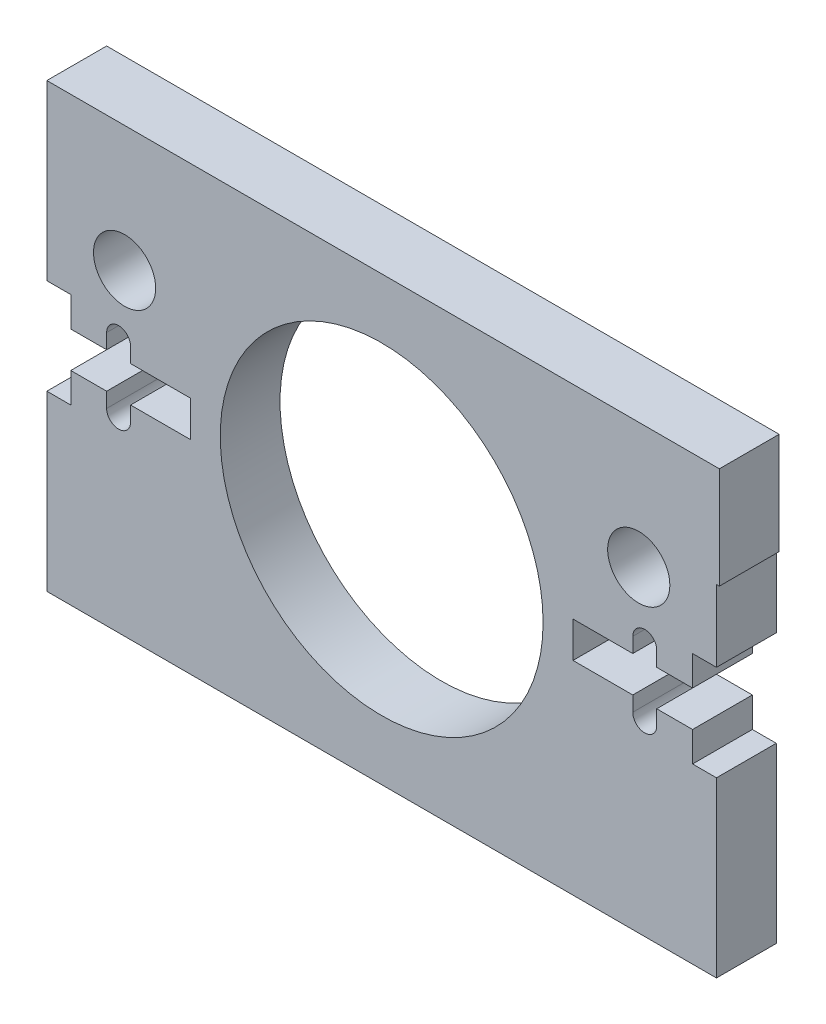
SolidWorks part; units mm, degrees
ref_plane "Front Plane" through (0, 0, 0) normal (0, 0, 1) x (1, 0, 0)
ref_plane "Top Plane" through (0, 0, 0) normal (0, 1, 0) x (1, 0, 0)
ref_plane "Right Plane" through (0, 0, 0) normal (1, 0, 0) x (0, 0, -1)
sketch "Sketch1" plane through (0, 0, 0) normal (0, 0, 1) x (1, 0, 0)
  line L1 (-28, -24.2015) -> (28, -24.2015)
  line L2 (-26, -14.2015) -> (26, -14.2015) construction
  line L3 (28, -4.2015) -> (28, -10.2015)
  line L4 (28, -4.2015) -> (26, -4.2015)
  line L5 (-28, -21.4252) -> (16.5776, 12.685) construction
  line L6 (-15.7126, 13.581) -> (28, -24.2015) construction
  line L7 (8.25, -1.4515) -> (3.5969, -1.4515)
  line L8 (8.25, -1.4515) -> (8.25, 3.2016)
  line L9 (8.25, 15.0485) -> (3.5969, 15.0485)
  line L10 (-8.25, -1.4515) -> (-8.25, 3.2016)
  line L11 (8.25, -1.4515) -> (-8.25, 15.0485) construction
  line L12 (8.25, 15.0485) -> (-8.25, -1.4515) construction
  line L13 (26, 2.9244) -> (12, 17.4269)
  line L14 (12, 17.4269) -> (-12, 17.4269)
  line L15 (-12, 17.4269) -> (-26, 2.9244)
  line L16 (0, 17.4269) -> (0, 6.7985) construction
  line L17 (-3.5969, 15.0485) -> (-8.25, 15.0485)
  line L18 (26, -4.2015) -> (26, 2.9244)
  line L19 (-8.25, 10.3954) -> (-8.25, 15.0485)
  line L20 (28, -10.2015) -> (26, -10.2015)
  line L21 (28, -18.2015) -> (26, -18.2015)
  line L22 (-28, -18.2015) -> (-28, -24.2015)
  line L23 (-22, -11.4515) -> (-22, -16.9515) construction
  line L24 (28, -18.2015) -> (28, -24.2015)
  line L25 (26, -10.2015) -> (26, -12.7015)
  line L26 (-28, -18.2015) -> (-26, -18.2015)
  line L27 (-26, -10.2015) -> (-26, -12.7015)
  line L28 (-28, -10.2015) -> (-26, -10.2015)
  line L29 (-26, -4.2015) -> (-26, 2.9244)
  line L30 (-28, -4.2015) -> (-28, -10.2015)
  line L31 (-28, -4.2015) -> (-26, -4.2015)
  line L32 (-26, -15.7015) -> (-23, -15.7015)
  line L33 (-26, -12.7015) -> (-23, -12.7015)
  line L34 (-3.5969, -1.4515) -> (-8.25, -1.4515)
  line L35 (32, -24.2015) -> (-32, -24.2015) construction
  line L36 (-21, -11.4515) -> (-21, -12.7015)
  line L37 (-23, -11.4515) -> (-23, -12.7015)
  line L38 (-16, -12.7015) -> (-16, -15.7015)
  line L39 (8.25, 10.3954) -> (8.25, 15.0485)
  line L40 (-23, -15.7015) -> (-23, -16.9515)
  line L41 (-21, -15.7015) -> (-21, -16.9515)
  line L42 (-21, -12.7015) -> (-16, -12.7015)
  line L43 (-21, -15.7015) -> (-16, -15.7015)
  line L44 (-26, -15.7015) -> (-26, -18.2015)
  line L45 (22, -11.4515) -> (22, -16.9515) construction
  line L46 (21, -15.7015) -> (16, -15.7015)
  line L47 (21, -12.7015) -> (16, -12.7015)
  line L48 (21, -15.7015) -> (21, -16.9515)
  line L49 (23, -15.7015) -> (23, -16.9515)
  line L50 (16, -12.7015) -> (16, -15.7015)
  line L51 (23, -11.4515) -> (23, -12.7015)
  line L52 (21, -11.4515) -> (21, -12.7015)
  line L53 (26, -12.7015) -> (23, -12.7015)
  line L54 (26, -15.7015) -> (23, -15.7015)
  line L55 (26, -15.7015) -> (26, -18.2015)
  circle A0 centre (21.5, -6.2015) radius 2.6
  circle A1 centre (-21.5, -6.2015) radius 2.6
  arc A2 (-21, -11.4515) -> (-23, -11.4515) centre (-22, -11.4515) ccw
  arc A3 (-23, -16.9515) -> (-21, -16.9515) centre (-22, -16.9515) ccw
  arc A4 (23, -16.9515) -> (21, -16.9515) centre (22, -16.9515) cw
  arc A5 (21, -11.4515) -> (23, -11.4515) centre (22, -11.4515) cw
  arc A6 (3.5969, 15.0485) -> (-3.5969, 15.0485) centre (0, 6.7985) ccw
  arc A7 (8.25, 10.3954) -> (3.5969, 15.0485) centre (0, 6.7985) ccw construction
  arc A8 (8.875, 5.3037) -> (8.875, 8.2933) centre (8.75, 6.7985) ccw
  arc A9 (-8.875, 8.2933) -> (-8.875, 5.3037) centre (-8.75, 6.7985) ccw
  arc A10 (8.875, 5.3037) -> (8.875, 8.2933) centre (8.75, 6.7985) ccw construction
  arc A11 (-8.875, 8.2933) -> (-8.875, 5.3037) centre (-8.75, 6.7985) ccw construction
  arc A12 (-8.25, 10.3954) -> (-8.25, 3.2016) centre (0, 6.7985) ccw
  arc A13 (-3.5969, -1.4515) -> (3.5969, -1.4515) centre (0, 6.7985) ccw
  arc A14 (8.25, 3.2016) -> (8.875, 5.3037) centre (0, 6.7985) ccw
  arc A15 (8.875, 8.2933) -> (8.25, 10.3954) centre (0, 6.7985) ccw
  point P0 (0, 0)
  point P6 (0, 6.7985)
  point P52 (-22, -14.2015)
  point P80 (22, -14.2015)
  dimension "D2" = 5.2
  dimension "D3" = 24
  dimension "D8" = 5.5
  dimension "D9" = 2
extrude "Boss-Extrude1" add sketch "Sketch1" along normal blind 5 contours L52 A5 L51 L53 L25 L20 L3 L4 L18 L13 L14 L15 L29 L31 L30 L28 L27 L33 L37 A2 L36 L42 L38 L43 L41 A3 L40 L32 L44 L26 L22 L1 L24 L21 L55 L54 L49 A4 L48 L46 L50 L47 A15 A8 A14 L8 L7 A13 L34 L10
sketch "Sketch2" plane through (0, 0, 5) normal (0, 0, 1) x (1, 0, 0)
  line L0 (-16, -14.2015) -> (16, -14.2015) construction
  line L4 (-28, -30.7015) -> (28, -30.7015)
  line L5 (-28, -30.7015) -> (-28, 2.2985)
  line L6 (-28, 2.2985) -> (28, 2.2985)
  line L7 (28, -30.7015) -> (28, 2.2985)
  line L8 (-28, -30.7015) -> (28, 2.2985) construction
  line L9 (-28, 2.2985) -> (28, -30.7015) construction
  line L11 (-29.6774, -33.6457) -> (40.0725, -33.6457)
  line L12 (-29.6774, -33.6457) -> (-29.6774, 19.8189)
  line L13 (-29.6774, 19.8189) -> (40.0725, 19.8189)
  line L14 (40.0725, -33.6457) -> (40.0725, 19.8189)
  circle A0 centre (0, -14.2015) radius 13.5
  dimension "D1" = 27
  dimension "D2" = 33
extrude "Cut-Extrude1" cut sketch "Sketch2" against normal blind 10 contours A0 | L11 L14 L13 L12 L7 L4 L5 L6
sketch "Sketch3" plane through (0, 0, 0) normal (0, 0, -1) x (-1, 0, 0)
  line L0 (28, -4.2015) -> (28, -10.2015) construction
  line L1 (-26, -0.7015) -> (-8.25, -0.7015)
  line L2 (-28.2413, -0.7015) -> (-28.2413, 4.2985)
  line L3 (-28.2413, 4.2985) -> (28, 4.2985)
  line L4 (28, -0.7015) -> (28, 4.2985)
  line L5 (8.25, -1.4515) -> (8.25, 2.2985) construction
  line L6 (-28, -27.7015) -> (28, -27.7015) construction
  line L7 (-8.25, -0.7015) -> (-8.25, -3.5156)
  line L8 (8.25, -0.7015) -> (26, -0.7015)
  line L9 (8.25, -0.7015) -> (8.25, -3.5156)
  line L10 (-8.25, -1.4515) -> (-8.25, 2.2985) construction
  line L11 (-28, -24.2015) -> (28, -24.2015)
  line L12 (-28, -24.2015) -> (-28, -32.7015)
  line L13 (-28, -32.7015) -> (28, -32.7015)
  line L14 (28, -24.2015) -> (28, -32.7015)
  line L15 (26, -4.2015) -> (26, 2.2985) construction
  line L17 (-28.2413, -0.7015) -> (-28.2413, -4.2015)
  line L18 (-28.2413, -4.2015) -> (-26, -4.2015)
  line L19 (-26, -0.7015) -> (-26, -4.2015)
  line L20 (28, -4.2015) -> (26, -4.2015)
  line L21 (28, -4.2015) -> (28, -0.7015)
  line L23 (26, -4.2015) -> (26, -0.7015)
  circle A0 centre (0, -14.2015) radius 13.5
  arc A1 (-4.4371, -1.4515) -> (-9.0692, -24.2015) centre (0, -14.2015) ccw construction
  line M1 (-8.25, -1.4515) -> (-8.25, 2.2985)
  line M2 (-8.25, 2.2985) -> (-26, 2.2985)
  line M3 (-26, 2.2985) -> (-26, -4.2015)
  line M4 (-26, -4.2015) -> (-28, -4.2015)
  line M22 (-28, -24.2015) -> (-9.0692, -24.2015)
  line M24 (-4.4371, -1.4515) -> (-8.25, -1.4515)
  dimension "D1" = 5
  dimension "D2" = 5
extrude "Boss-Extrude2" add sketch "Sketch3" against normal blind 5 contours A0 L9 L8 L23 L20 L21 L4 L3 L2 L17 L18 M4 M3 M2 M1 M24 | L6 L12 L13 L14 | A0 L6 L14 L11 | L12 L6 A0 M22
